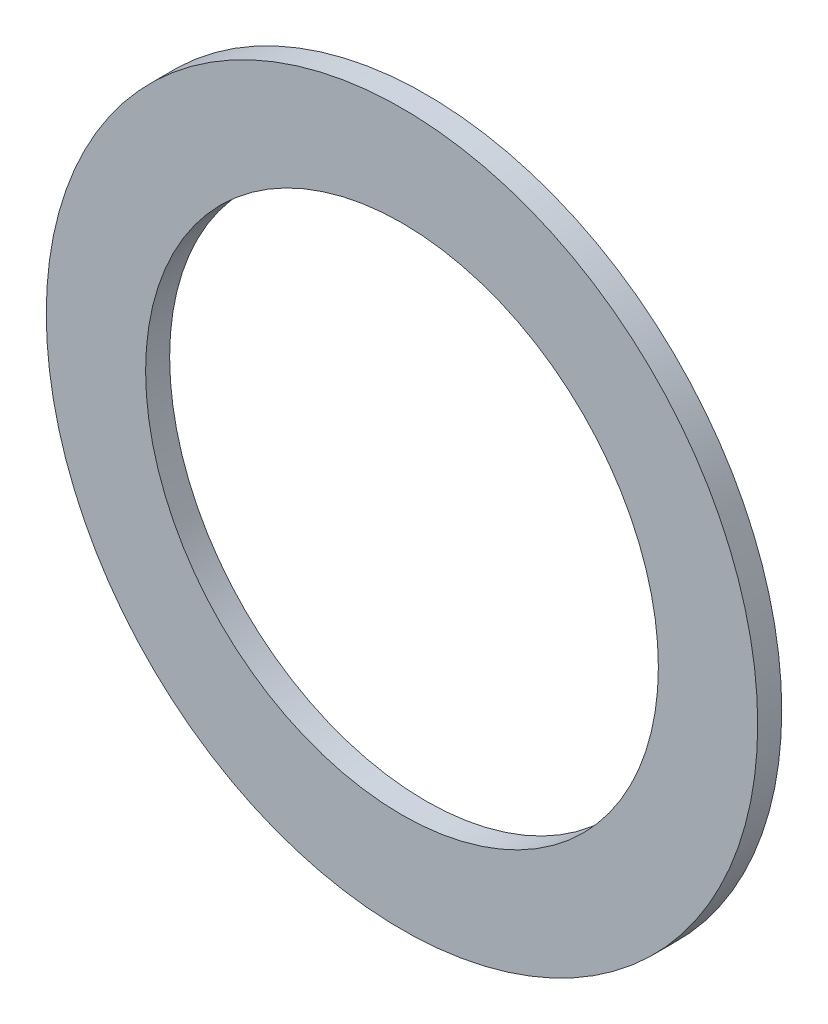
SolidWorks part; units mm, degrees
ref_plane "Спереди" through (0, 0, 0) normal (0, 0, 1) x (1, 0, 0)
ref_plane "Сверху" through (0, 0, 0) normal (0, 1, 0) x (1, 0, 0)
ref_plane "Справа" through (0, 0, 0) normal (1, 0, 0) x (0, 0, -1)
sketch "Эскиз1" plane through (0, 0, 0) normal (0, 0, 1) x (1, 0, 0)
  circle A0 centre (0, 0) radius 22.2
  circle A1 centre (0, 0) radius 16
extrude "Stack_washer" add sketch "Эскиз1" along normal blind 1.5 from offset 15
